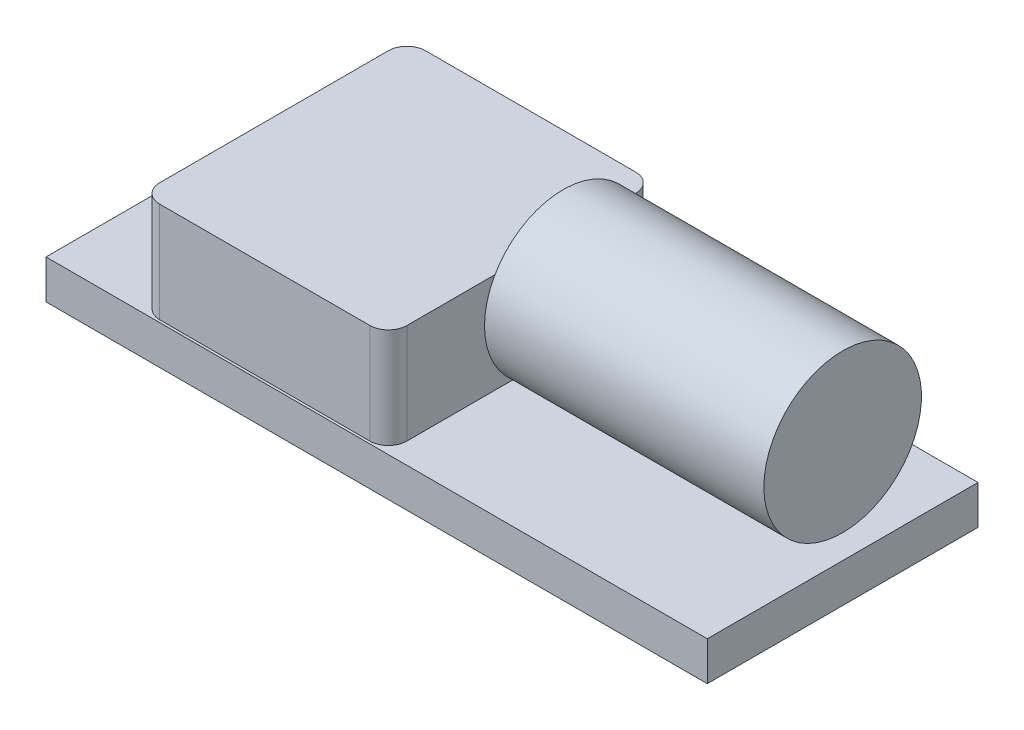
SolidWorks part; units mm, degrees
ref_plane "Front Plane" through (0, 0, 0) normal (0, 0, 1) x (1, 0, 0)
ref_plane "Top Plane" through (0, 0, 0) normal (0, 1, 0) x (1, 0, 0)
ref_plane "Right Plane" through (0, 0, 0) normal (1, 0, 0) x (0, 0, -1)
sketch "Sketch1" plane through (0, 0, 0) normal (0, 1, 0) x (1, 0, 0)
  line L1 (-13.589, -5.5626) -> (13.589, -5.5626)
  line L2 (-13.589, -5.5626) -> (-13.589, 5.5626)
  line L3 (-13.589, 5.5626) -> (13.589, 5.5626)
  line L4 (13.589, -5.5626) -> (13.589, 5.5626)
  line L5 (-13.589, -5.5626) -> (13.589, 5.5626) construction
  line L6 (-13.589, 5.5626) -> (13.589, -5.5626) construction
  point P0 (0, 0)
  dimension "D1" = 11.1252
  dimension "D2" = 27.178
extrude "Boss-Extrude1" add sketch "Sketch1" against normal blind 1.6002
sketch "Sketch2" plane through (0, 0, 0) normal (0, 1, 0) x (1, 0, 0)
  line L0 (-13.589, 5.5626) -> (-13.589, -5.5626) construction
  line L1 (-9.017, -5.461) -> (-0.381, -5.461)
  line L2 (-9.779, -4.699) -> (-9.779, 4.699)
  line L3 (-9.017, 5.461) -> (-0.381, 5.461)
  line L4 (0.381, -4.699) -> (0.381, 4.699)
  line L5 (-9.779, -5.461) -> (0.381, 5.461) construction
  line L6 (-9.779, 5.461) -> (0.381, -5.461) construction
  arc A0 (-0.381, 5.461) -> (0.381, 4.699) centre (-0.381, 4.699) cw
  arc A1 (0.381, -4.699) -> (-0.381, -5.461) centre (-0.381, -4.699) cw
  arc A2 (-9.017, -5.461) -> (-9.779, -4.699) centre (-9.017, -4.699) cw
  arc A3 (-9.779, 4.699) -> (-9.017, 5.461) centre (-9.017, 4.699) cw
  point P0 (-4.699, 0)
  point P7 (0, 0)
  dimension "D4" = 0.762
  dimension "D1" = 10.922
  dimension "D2" = 10.16
  dimension "D3" = 3.81
extrude "Boss-Extrude2" add sketch "Sketch2" along normal blind 4.1148
sketch "Sketch3" plane through (0, 0, 0) normal (0, 0, 1) x (1, 0, 0)
  line L0 (-13.589, -1.6002) -> (13.589, -1.6002) construction
  line L1 (2.1082, 4.2291) -> (13.589, 4.2291)
  line L2 (2.1082, 4.2291) -> (2.1082, 7.4676)
  line L3 (2.1082, 7.4676) -> (13.589, 7.4676)
  line L4 (13.589, 4.2291) -> (13.589, 7.4676)
  line L5 (2.1082, 4.2291) -> (13.589, 7.4676) construction
  line L6 (2.1082, 7.4676) -> (13.589, 4.2291) construction
  line L7 (13.589, -1.6002) -> (13.589, 0) construction
  point P0 (7.8486, 5.8483)
  point P5 (13.8483, 0.5379)
  dimension "D1" = 11.4808
  dimension "D2" = 9.0678
  dimension "D3" = 3.2385
revolve "Revolve1" add sketch "Sketch3" angle 360 about L1
